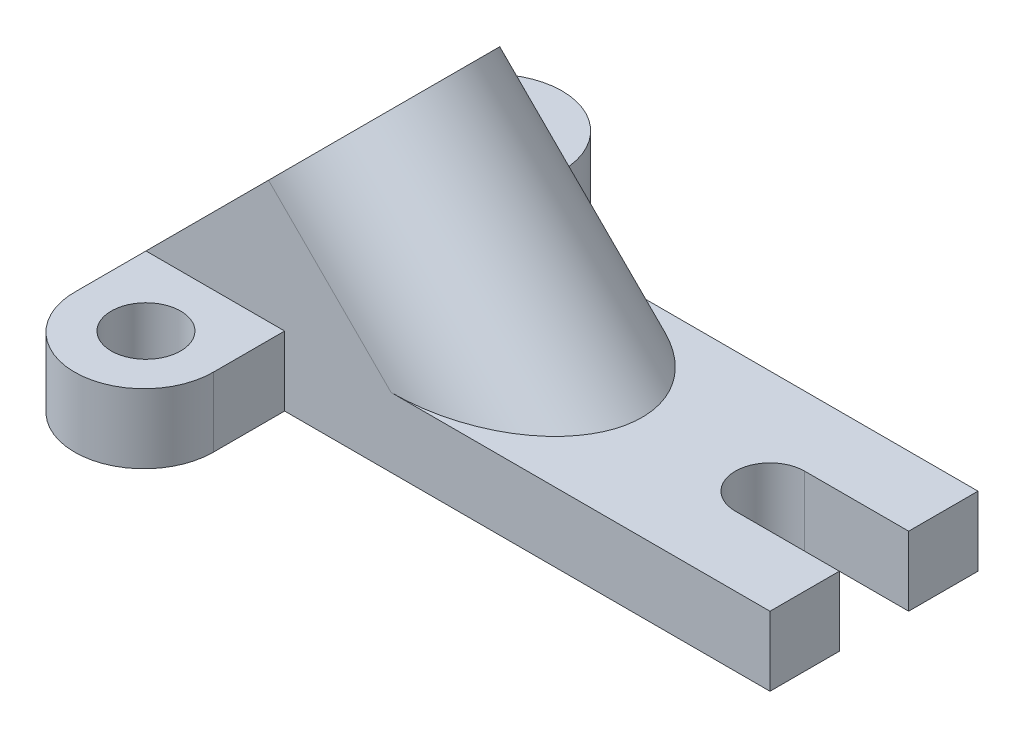
SolidWorks part; units mm, degrees
ref_plane "Front Plane" through (0, 0, 0) normal (0, 0, 1) x (1, 0, 0)
ref_plane "Top Plane" through (0, 0, 0) normal (0, 1, 0) x (1, 0, 0)
ref_plane "Right Plane" through (0, 0, 0) normal (1, 0, 0) x (0, 0, -1)
sketch "Sketch1" plane through (0, 0, 0) normal (0, 1, 0) x (1, 0, 0)
  line L1 (0, 60) -> (140, 60)
  line L2 (140, 60) -> (140, 0)
  line L3 (140, 0) -> (0, 0)
  line L4 (0, 60) -> (0, 80)
  line L7 (0, 0) -> (0, -20.5636)
  line L8 (-39.999, 80) -> (-39.999, -20)
  arc A0 (-39.999, 80) -> (0, 80) centre (-19.9995, 80) cw
  arc A1 (-39.999, -20) -> (0, -20.5636) centre (-20.0035, -20.5636) ccw
  point P6 (0, 0)
  dimension "D4" = 100.5636
  dimension "D5" = 80
  dimension "D6" = 28.688
  dimension "D1" = 60
  dimension "D2" = 140
  dimension "D3" = 179.999
  dimension "D7" = 28.2839
extrude "Boss-Extrude2" add sketch "Sketch1" along normal blind 20
sketch "Sketch2" plane through (0, 20, 0) normal (0, 1, 0) x (1, 0, 0)
  circle A0 centre (-19.9995, 80) radius 10
  circle A1 centre (-19.9995, -20) radius 10
  dimension "D1" = 20
  dimension "D2" = 20
  dimension "D3" = 20
  dimension "D4" = 100
extrude "Cut-Extrude1" cut sketch "Sketch2" against normal through all
ref_plane "Plane2" through (-29.9995, 29.9995, 0) normal (-0.7071, 0.7071, 0) x (0, 0, 1)
sketch "Sketch4" plane through (-29.9995, 29.9995, 0) normal (-0.7071, 0.7071, 0) x (0, 0, 1)
  line L0 (-60, -14.1414) -> (-60, 35.8586)
  line L1 (0, -14.1414) -> (0, 35.8586)
  line L2 (-60, -14.1414) -> (0, -14.1414)
  arc A0 (-60, 35.8586) -> (0, 35.8586) centre (-30, 35.8586) cw
  dimension "D3" = 30
  dimension "D1" = 50
  dimension "D2" = 60
extrude "Boss-Extrude3" add sketch "Sketch4" against normal up to surface (50 mm away)
sketch "Sketch5" plane through (-29.9995, 29.9995, 0) normal (-0.7071, 0.7071, 0) x (0, 0, 1)
  circle A1 centre (-30, 35.8586) radius 15
  dimension "D1" = 30
extrude "Cut-Extrude3" cut sketch "Sketch5" against normal up to surface (63.2843 mm away)
sketch "Sketch6" plane through (0, 20, 0) normal (0, 1, 0) x (1, 0, 0)
  line L0 (140, 40) -> (110, 40)
  line L1 (140, 0) -> (140, 60) construction
  line L2 (140, 20) -> (140, 40)
  line L3 (140, 20) -> (110, 20)
  arc A0 (110, 20) -> (110, 40) centre (110, 30) cw
  dimension "D1" = 30
  dimension "D2" = 20
extrude "Cut-Extrude4" cut sketch "Sketch6" against normal through all
